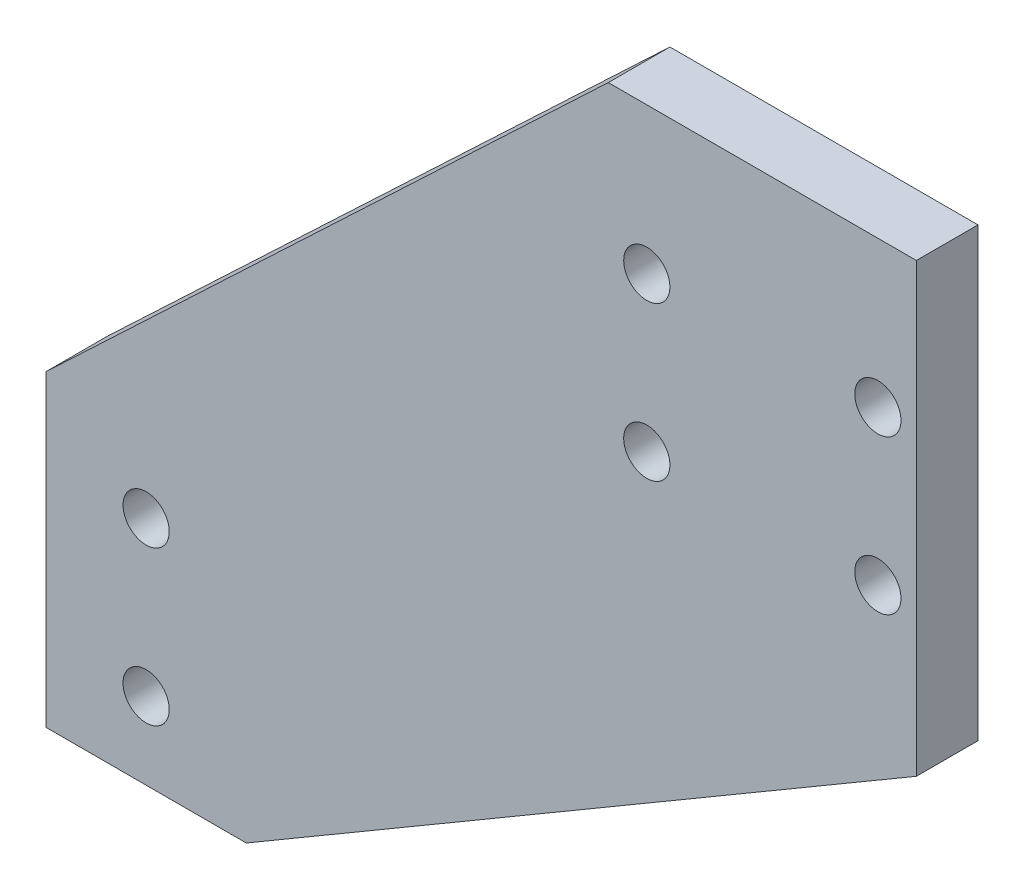
SolidWorks part; units mm, degrees
ref_plane "前视基准面" through (0, 0, 0) normal (0, 0, 1) x (1, 0, 0)
ref_plane "上视基准面" through (0, 0, 0) normal (0, 1, 0) x (1, 0, 0)
ref_plane "右视基准面" through (0, 0, 0) normal (1, 0, 0) x (0, 0, -1)
other "Configuration Table"
sketch "草图1" plane through (0, 0, 0) normal (0, 0, 1) x (1, 0, 0)
  line L0 (0, 0) -> (13, 0)
  line L1 (13, 0) -> (56.5, 25.5)
  line L2 (56.5, 25.5) -> (56.5, 54.5)
  line L3 (56.5, 54.5) -> (36.5, 54.5)
  line L4 (36.5, 54.5) -> (0, 20)
  line L5 (0, 20) -> (0, 0)
  line L6 (0, 20) -> (13, 20) construction
  line L7 (13, 20) -> (13, 0) construction
  line L8 (36.5, 54.5) -> (36.5, 25.5) construction
  line L9 (36.5, 25.5) -> (56.5, 25.5) construction
  line L10 (0, 10) -> (13, 10) construction
  line L11 (6.5, 10) -> (6.5, 15) construction
  line L12 (36.5, 40) -> (56.5, 40) construction
  line L13 (46.5, 40) -> (46.5, 54.5) construction
  circle A0 centre (6.5, 15) radius 1.5
  circle A1 centre (6.5, 5) radius 1.5
  circle A2 centre (39, 35) radius 1.5
  circle A3 centre (54, 35) radius 1.5
  circle A4 centre (39, 45) radius 1.5
  circle A5 centre (54, 45) radius 1.5
  dimension "D1" = 3
  dimension "D2" = 3
  dimension "D5" = 10
  dimension "D6" = 15
  dimension "D9" = 10
  dimension "D3" = 20
  dimension "D4" = 29
  dimension "D7" = 20
  dimension "D8" = 13
  dimension "D10" = 40
  dimension "D11" = 30
extrude "凸台-拉伸1" add sketch "草图1" along normal blind 4
